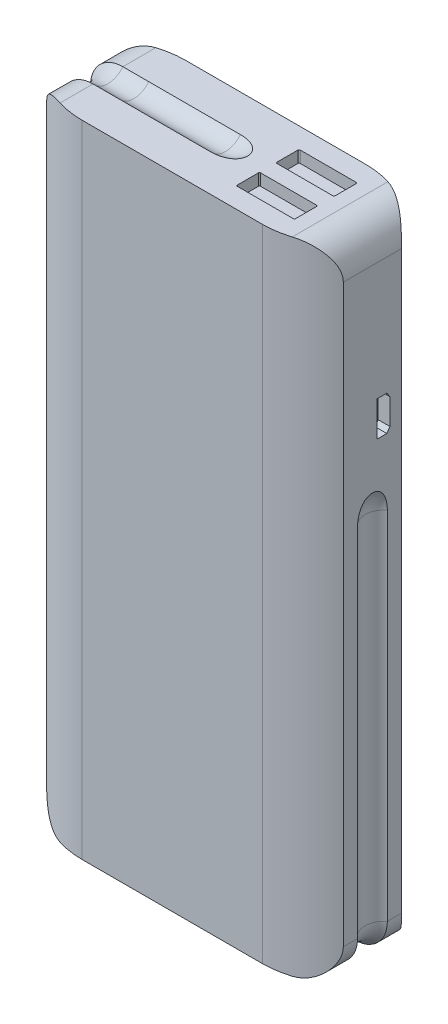
SolidWorks part; units mm, degrees
ref_plane "Front Plane" through (0, 0, 0) normal (0, 0, 1) x (1, 0, 0)
ref_plane "Top Plane" through (0, 0, 0) normal (0, 1, 0) x (1, 0, 0)
ref_plane "Right Plane" through (0, 0, 0) normal (1, 0, 0) x (0, 0, -1)
sketch "Sketch1" plane through (0, 0, 0) normal (0, 1, 0) x (1, 0, 0)
  line L0 (-32.385, 0) -> (32.385, 0) construction
  line L1 (-32.385, -11.303) -> (32.385, -11.303)
  line L2 (-32.385, -11.303) -> (-32.385, 11.303)
  line L3 (-32.385, 11.303) -> (32.385, 11.303)
  line L4 (32.385, -11.303) -> (32.385, 11.303)
  line L5 (-32.385, -11.303) -> (32.385, 11.303) construction
  line L6 (-32.385, 11.303) -> (32.385, -11.303) construction
  line L7 (0, 11.303) -> (0, -11.303) construction
  arc A1 (-19.685, -11.303) -> (-32.385, -6.35) centre (-19.685, 7.4556) cw
  arc A2 (-19.685, 11.303) -> (-32.385, 6.35) centre (-19.685, -7.4556) ccw
  arc A3 (19.685, 11.303) -> (32.385, 6.35) centre (19.685, -7.4556) cw
  arc A4 (19.685, -11.303) -> (32.385, -6.35) centre (19.685, 7.4556) ccw
  point P0 (0, 0)
  dimension "D3" = 4.953
  dimension "D1" = 64.77
  dimension "D2" = 22.606
  dimension "D4" = 12.7
extrude "Boss-Extrude1" add sketch "Sketch1" along normal blind 139.7 contours L1 A4 L4 A3 L3 A2 L2 A1
sketch "Sketch2" plane through (0, 0, 11.303) normal (0, 0, 1) x (1, 0, 0)
  line L0 (-32.385, 139.7) -> (-32.385, 0) construction
  line L1 (32.385, 139.7) -> (32.385, 0) construction
  line L2 (-32.385, 132.6388) -> (-32.385, 7.0612)
  line L3 (32.385, 132.6388) -> (32.385, 7.0612)
  line L5 (32.385, 0) -> (-32.385, 0)
  line L6 (32.385, 0) -> (32.385, 139.7)
  line L7 (32.385, 139.7) -> (-32.385, 139.7)
  line L12 (25.3238, 0) -> (-25.3238, 0)
  line L13 (25.3238, 139.7) -> (-25.3238, 139.7)
  line L14 (-32.385, 0) -> (-32.385, 139.7)
  arc A0 (-32.385, 132.6388) -> (-25.3238, 139.7) centre (-25.3238, 132.6388) cw
  arc A1 (-32.385, 7.0612) -> (-25.3238, 0) centre (-25.3238, 7.0612) ccw
  arc A2 (32.385, 7.0612) -> (25.3238, 0) centre (25.3238, 7.0612) cw
  arc A3 (32.385, 132.6388) -> (25.3238, 139.7) centre (25.3238, 132.6388) ccw
  point P2 (-32.385, 139.7)
  point P18 (32.385, 0)
  dimension "D1" = 7.0612
extrude "Cut-Extrude1" cut sketch "Sketch2" against normal through all contours L14 A0 L7 | A3 L6 L7 | L6 A2 L5 | A1 L14 L5
sketch "Sketch4" plane through (0, 139.7, 0) normal (0, 1, 0) x (1, 0, 0)
  line L0 (0, 0) -> (26.2714, 0) construction
  line L1 (21.971, -6.858) -> (9.779, -6.858)
  line L2 (22.225, -6.604) -> (22.225, -2.032)
  line L3 (21.971, -1.778) -> (9.779, -1.778)
  line L4 (9.525, -6.604) -> (9.525, -2.032)
  line L5 (32.385, 6.35) -> (32.385, -6.35) construction
  line L6 (9.525, 6.604) -> (9.525, 2.032)
  line L7 (21.971, 1.778) -> (9.779, 1.778)
  line L8 (22.225, 6.604) -> (22.225, 2.032)
  line L9 (21.971, 6.858) -> (9.779, 6.858)
  arc A0 (22.225, -2.032) -> (21.971, -1.778) centre (21.971, -2.032) ccw
  arc A1 (9.779, -1.778) -> (9.525, -2.032) centre (9.779, -2.032) ccw
  arc A2 (9.779, -6.858) -> (9.525, -6.604) centre (9.779, -6.604) cw
  arc A3 (21.971, -6.858) -> (22.225, -6.604) centre (21.971, -6.604) ccw
  arc A4 (21.971, 6.858) -> (22.225, 6.604) centre (21.971, 6.604) cw
  arc A5 (9.779, 6.858) -> (9.525, 6.604) centre (9.779, 6.604) ccw
  arc A6 (9.779, 1.778) -> (9.525, 2.032) centre (9.779, 2.032) cw
  arc A7 (22.225, 2.032) -> (21.971, 1.778) centre (21.971, 2.032) cw
  point P11 (22.225, -1.778)
  point P16 (9.525, -6.858)
  point P19 (22.225, -6.858)
  point P32 (22.225, 6.858)
  point P33 (9.525, 6.858)
  point P34 (22.225, 1.778)
  dimension "D5" = 0.254
  dimension "D1" = 12.7
  dimension "D2" = 5.08
  dimension "D3" = 1.778
  dimension "D4" = 10.16
extrude "Cut-Extrude2" cut sketch "Sketch4" against normal blind 2.54
sketch "Sketch3" plane through (0, 0, 0) normal (0, 0, 1) x (1, 0, 0)
  line L8 (-19.685, 142.24) -> (0.3175, 142.24)
  line L10 (34.925, 84.7725) -> (34.925, 7.0612)
  line L11 (39.0525, 88.9) -> (43.1995, 88.9)
  line L12 (4.445, 146.3675) -> (4.445, 151.2241)
  line L16 (25.3238, 142.24) -> (19.685, 142.24)
  line L17 (19.685, 142.24) -> (-19.685, 142.24)
  line L18 (-19.685, 142.24) -> (-25.3238, 142.24)
  line L19 (-34.925, 132.6388) -> (-34.925, 7.0612)
  line L20 (-25.3238, -2.54) -> (-19.685, -2.54)
  line L21 (-19.685, -2.54) -> (19.685, -2.54)
  line L22 (19.685, -2.54) -> (25.3238, -2.54)
  line L23 (34.925, 7.0612) -> (34.925, 132.6388)
  line L26 (-19.685, 142.24) -> (-25.3238, 142.24)
  line L27 (-34.925, 132.6388) -> (-34.925, 7.0612)
  line L28 (-25.3238, -2.54) -> (-19.685, -2.54)
  line L29 (-19.685, -2.54) -> (19.685, -2.54)
  line L30 (19.685, -2.54) -> (25.3238, -2.54)
  arc A4 (0.3175, 142.24) -> (4.445, 146.3675) centre (0.3175, 146.3675) ccw
  arc A5 (39.0525, 88.9) -> (34.925, 84.7725) centre (39.0525, 84.7725) ccw
  arc A8 (34.925, 132.6388) -> (25.3238, 142.24) centre (25.3238, 132.6388) ccw
  arc A9 (-25.3238, 142.24) -> (-34.925, 132.6388) centre (-25.3238, 132.6388) ccw
  arc A10 (-34.925, 7.0612) -> (-25.3238, -2.54) centre (-25.3238, 7.0612) ccw
  arc A11 (25.3238, -2.54) -> (34.925, 7.0612) centre (25.3238, 7.0612) ccw
  arc A13 (-25.3238, 142.24) -> (-34.925, 132.6388) centre (-25.3238, 132.6388) ccw
  arc A14 (-34.925, 7.0612) -> (-25.3238, -2.54) centre (-25.3238, 7.0612) ccw
  arc A15 (25.3238, -2.54) -> (34.925, 7.0612) centre (25.3238, 7.0612) ccw
  point P0 (4.445, 142.24)
  point P1 (34.925, 88.9)
  point P8 (4.445, 142.24)
  point P11 (34.925, 88.9)
  dimension "D4" = 4.1275
  dimension "D2" = 5.08
  dimension "D3" = 81.8388
  dimension "D1" = 2.54
ref_plane "Plane1" through (43.1995, 0, 0) normal (1, 0, 0) x (0, 0, -1)
sketch "Sketch5" plane through (43.1995, 0, 0) normal (1, 0, 0) x (0, 0, -1)
  circle A0 centre (0, 88.9) radius 4.1275
  dimension "D1" = 8.255
sweep "Cut-Sweep1" cut profiles "Sketch5" path "Sketch3"
sketch "Sketch6" plane through (32.385, 0, 0) normal (1, 0, 0) x (0, 0, -1)
  line L0 (1.016, 99.3054) -> (1.016, 106.9254)
  line L1 (1.016, 106.9254) -> (3.1369, 106.9254)
  line L2 (3.1369, 106.9254) -> (3.81, 105.9348)
  line L3 (3.81, 105.9348) -> (3.81, 100.296)
  line L4 (3.81, 100.296) -> (3.1369, 99.3054)
  line L5 (3.1369, 99.3054) -> (1.016, 99.3054)
  line L6 (6.35, 132.6388) -> (6.35, 7.0612) construction
  point P6 (3.81, 103.1154)
  point P7 (1.016, 103.1154)
  point P8 (0, 0)
  point P9 (5.0924, 103.1154)
  point P10 (4.9793, 106.0564)
  point P11 (5.011, 100.5778)
  point P12 (0, 0)
  point P13 (0, 0)
  dimension "D1" = 7.62
  dimension "D2" = 2.1209
  dimension "D3" = 2.1209
  dimension "D4" = 2.794
  dimension "D5" = 5.6388
  dimension "D6" = 3.81
  dimension "D7" = 2.54
extrude "Cut-Extrude3" cut sketch "Sketch6" against normal blind 2.54
